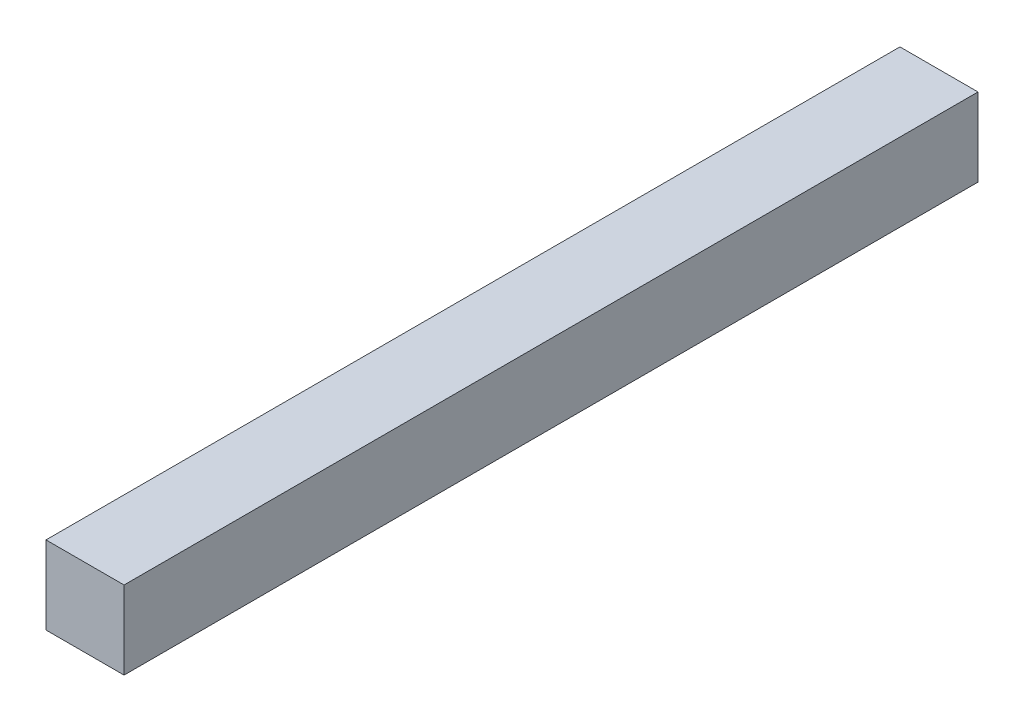
SolidWorks part; units mm, degrees
ref_plane "Front Plane" through (0, 0, 0) normal (0, 0, 1) x (1, 0, 0)
ref_plane "Top Plane" through (0, 0, 0) normal (0, 1, 0) x (1, 0, 0)
ref_plane "Right Plane" through (0, 0, 0) normal (1, 0, 0) x (0, 0, -1)
sketch "Sketch1" plane through (0, 0, 0) normal (0, 0, 1) x (1, 0, 0)
  line L1 (-1.6, -1.6) -> (1.6, -1.6)
  line L2 (-1.6, -1.6) -> (-1.6, 1.6)
  line L3 (-1.6, 1.6) -> (1.6, 1.6)
  line L4 (1.6, -1.6) -> (1.6, 1.6)
  line L5 (-1.6, -1.6) -> (1.6, 1.6) construction
  line L6 (-1.6, 1.6) -> (1.6, -1.6) construction
  point P0 (0, 0)
  dimension "D1" = 3.2
extrude "Boss-Extrude1" add sketch "Sketch1" along normal blind 35
sketch "Sketch2" plane through (0, 0, 35) normal (0, 0, 1) x (1, 0, 0)
  circle A0 centre (0, 0) radius 2.2627
